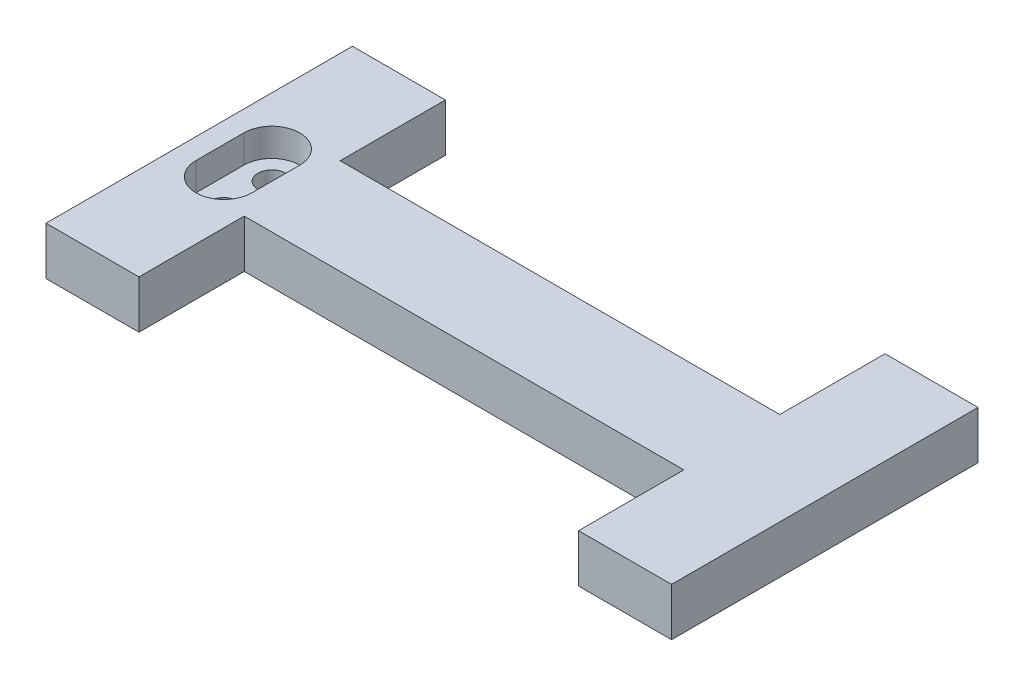
SolidWorks part; units mm, degrees
ref_plane "Front Plane" through (0, 0, 0) normal (0, 0, 1) x (1, 0, 0)
ref_plane "Top Plane" through (0, 0, 0) normal (0, 1, 0) x (1, 0, 0)
ref_plane "Right Plane" through (0, 0, 0) normal (1, 0, 0) x (0, 0, -1)
sketch "Sketch2" plane through (0, 0, 0) normal (0, 1, 0) x (1, 0, 0)
  line L0 (0, 0) -> (0, 6)
  line L1 (-27.5, -6) -> (27.5, -6)
  line L2 (-27.5, -6) -> (-27.5, 6)
  line L3 (-27.5, 6) -> (27.5, 6)
  line L4 (27.5, -6) -> (27.5, 6)
  line L5 (-27.5, -6) -> (27.5, 6) construction
  line L6 (-27.5, 6) -> (27.5, -6) construction
  line L7 (-39.1346, 19.1707) -> (-27.5, 19.1707)
  line L8 (-39.1346, 19.1707) -> (-39.1346, -19.1707)
  line L9 (-39.1346, -19.1707) -> (-27.5, -19.1707)
  line L10 (-27.5, 19.1707) -> (-27.5, -19.1707)
  line L11 (-39.1346, 19.1707) -> (-27.5, -19.1707) construction
  line L12 (-39.1346, -19.1707) -> (-27.5, 19.1707) construction
  line L17 (0, 6) -> (0, -6)
  line L18 (39.1346, -19.1707) -> (27.5, -19.1707)
  line L19 (27.5, 19.1707) -> (27.5, -19.1707)
  line L20 (39.1346, 19.1707) -> (27.5, 19.1707)
  line L21 (39.1346, 19.1707) -> (39.1346, -19.1707)
  point P0 (0, 0)
  point P6 (-33.3173, 0)
  point P11 (30.1442, 0)
  dimension "D1" = 55
  dimension "D2" = 12
  dimension "D3" = 33.3173
  dimension "D4" = 38.3413
extrude "Boss-Extrude1" add sketch "Sketch2" along normal blind 6 contours L10 L7 L8 L9 L2 | L17 L0 L3 L2 L1 | L0 L17 L1 L4 L3 | L21 L20 L19 L4 L18
sketch "Sketch3" plane through (0, 6, 0) normal (0, 1, 0) x (1, 0, 0)
  line L0 (-33.0442, 3) -> (-33.0442, -3) construction
  line L1 (-29.5442, 3) -> (-29.5442, -3)
  line L2 (-36.5442, 3) -> (-36.5442, -3)
  line L3 (-27.5, 6) -> (27.5, 6) construction
  arc A0 (-29.5442, 3) -> (-36.5442, 3) centre (-33.0442, 3) ccw
  arc A1 (-36.5442, -3) -> (-29.5442, -3) centre (-33.0442, -3) ccw
  point P2 (-33.0442, 0)
  dimension "D1" = 3
  dimension "D2" = 6
  dimension "D3" = 3.5
extrude "Cut-Extrude2" cut sketch "Sketch3" against normal blind 3.5
sketch "Sketch5" plane through (0, 2.5, 0) normal (0, 1, 0) x (1, 0, 0)
  circle A0 centre (-33.0442, 3) radius 1.75
  circle A1 centre (-33.0442, -3) radius 1.75
  arc A4 (-29.5442, 3) -> (-36.5442, 3) centre (-33.0442, 3) ccw construction
  dimension "D4" = 3.5
  dimension "D5" = 3.5
  dimension "D6" = 0
  dimension "D1" = 3.5
  dimension "D2" = 6
  dimension "D3" = 3.5
extrude "Cut-Extrude3" cut sketch "Sketch5" against normal blind 4
